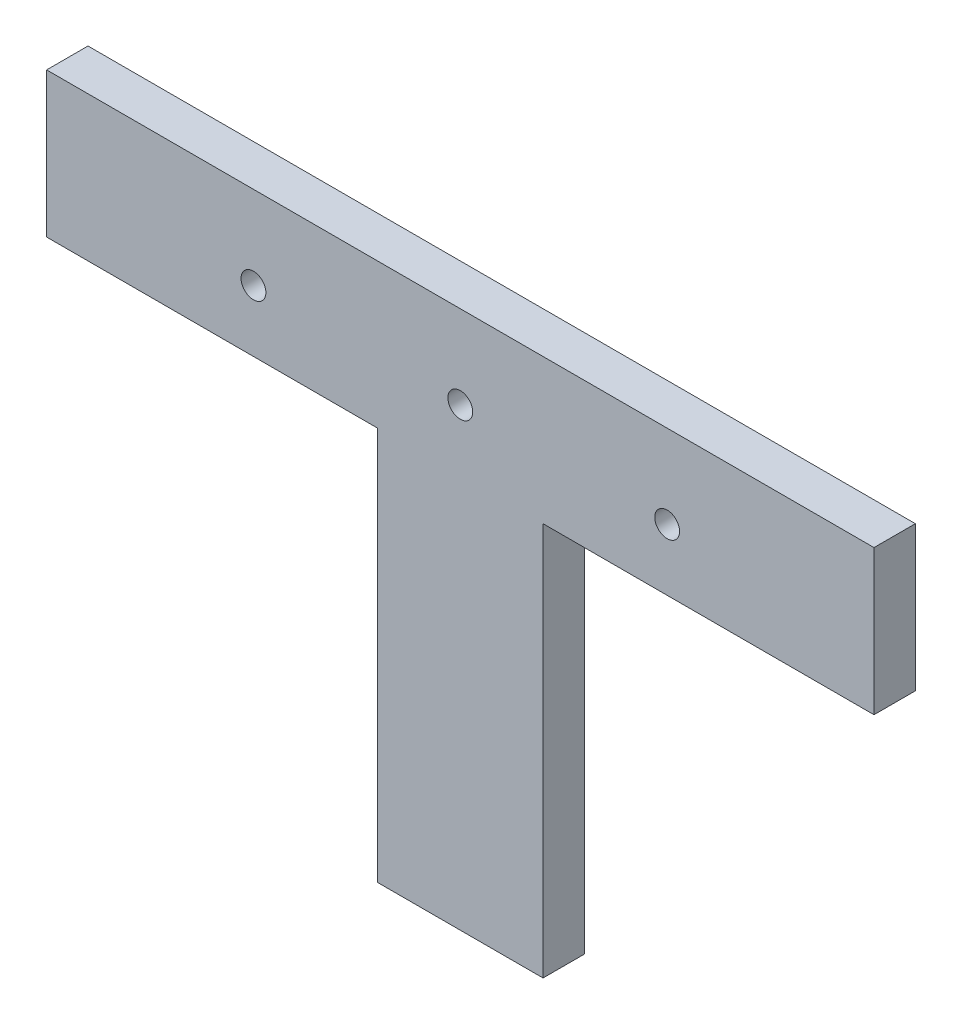
SolidWorks part; units mm, degrees
ref_plane "前基準面" through (0, 0, 0) normal (0, 0, 1) x (1, 0, 0)
ref_plane "上基準面" through (0, 0, 0) normal (0, 1, 0) x (1, 0, 0)
ref_plane "右基準面" through (0, 0, 0) normal (1, 0, 0) x (0, 0, -1)
sketch "草圖1" plane through (0, 0, 0) normal (0, 0, 1) x (1, 0, 0)
  line L0 (-40.1551, 7.2196) -> (-80.1551, 7.2196)
  line L1 (-80.1551, 7.2196) -> (-80.1551, 102.3297)
  line L2 (-80.1551, 102.3297) -> (-160.1551, 102.3297)
  line L3 (-160.1551, 102.3297) -> (-160.1551, 137.3297)
  line L4 (-160.1551, 137.3297) -> (39.8449, 137.3297)
  line L5 (39.8449, 137.3297) -> (39.8449, 102.3297)
  line L6 (39.8449, 102.3297) -> (-40.1551, 102.3297)
  line L7 (-40.1551, 102.3297) -> (-40.1551, 7.2196)
  line L8 (-60.1551, 137.3297) -> (-60.1551, 151.4898) construction
  line L9 (-60.1551, 7.2196) -> (-60.1551, -12.7977) construction
  dimension "D1" = 200
  dimension "D2" = 35
  dimension "D3" = 40
extrude "填料-伸長1" add sketch "草圖1" along normal blind 10
sketch "草圖2" plane through (0, 0, 10) normal (0, 0, 1) x (1, 0, 0)
  line L0 (39.8449, 102.3297) -> (39.8449, 137.3297) construction
  circle A0 centre (-10.1551, 117.1895) radius 3
  dimension "D1" = 6
  dimension "D6" = 50
extrude "除料-伸長1" cut sketch "草圖2" against normal up to surface (10 mm away) up to face at (-60.1551, 87.3022, 0)
pattern_linear "LPattern1" count 3 spacing 50 along (-1, 0, 0) of "除料-伸長1"
